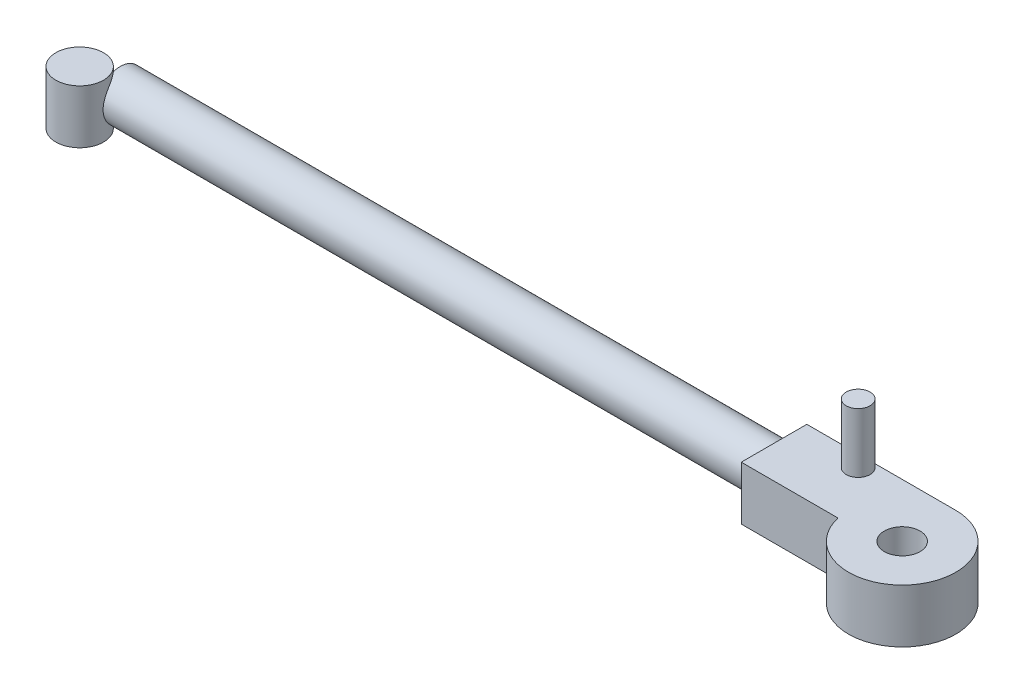
SolidWorks part; units mm, degrees
ref_plane "Front Plane" through (0, 0, 0) normal (0, 0, 1) x (1, 0, 0)
ref_plane "Top Plane" through (0, 0, 0) normal (0, 1, 0) x (1, 0, 0)
ref_plane "Right Plane" through (0, 0, 0) normal (1, 0, 0) x (0, 0, -1)
sketch "Sketch1" plane through (0, 0, 0) normal (0, 1, 0) x (1, 0, 0)
  line L0 (0, 9) -> (-25, 9)
  line L1 (-25, 9) -> (-25, -2)
  line L2 (-25, -2) -> (-8.775, -2)
  circle A0 centre (0, 0) radius 9
  dimension "D1" = 18
  dimension "D2" = 11
  dimension "D3" = 25
extrude "Boss-Extrude1" add sketch "Sketch1" along normal blind 9 contours A0 L0 L1 L2 | A0
sketch "Sketch2" plane through (0, 0, 0) normal (0, -1, 0) x (1, 0, 0)
  circle A0 centre (0, 0) radius 3
  dimension "D1" = 6
extrude "Cut-Extrude1" cut sketch "Sketch2" against normal through all
sketch "Sketch3" plane through (0, 0, 0) normal (0, 1, 0) x (1, 0, 0)
  circle A0 centre (-138, 0) radius 4
  dimension "D1" = 8
  dimension "D2" = 138
extrude "Boss-Extrude2" add sketch "Sketch3" along normal up to surface (9 mm away) separate body up to face at (0, 9, -3)
sketch "Sketch4" plane through (-25, 0, 0) normal (-1, 0, 0) x (0, 0, 1)
  circle A0 centre (-3.7848, 4.7433) radius 3.8526
extrude "Boss-Extrude3" add sketch "Sketch4" along normal blind 110
sketch "Sketch5" plane through (0, 9, 0) normal (0, 1, 0) x (1, 0, 0)
  line L0 (0, 9) -> (-25, 9) construction
  circle A0 centre (-14.3875, 7) radius 2
  dimension "D1" = 4
  dimension "D2" = 16
extrude "Boss-Extrude4" add sketch "Sketch5" along normal blind 10
